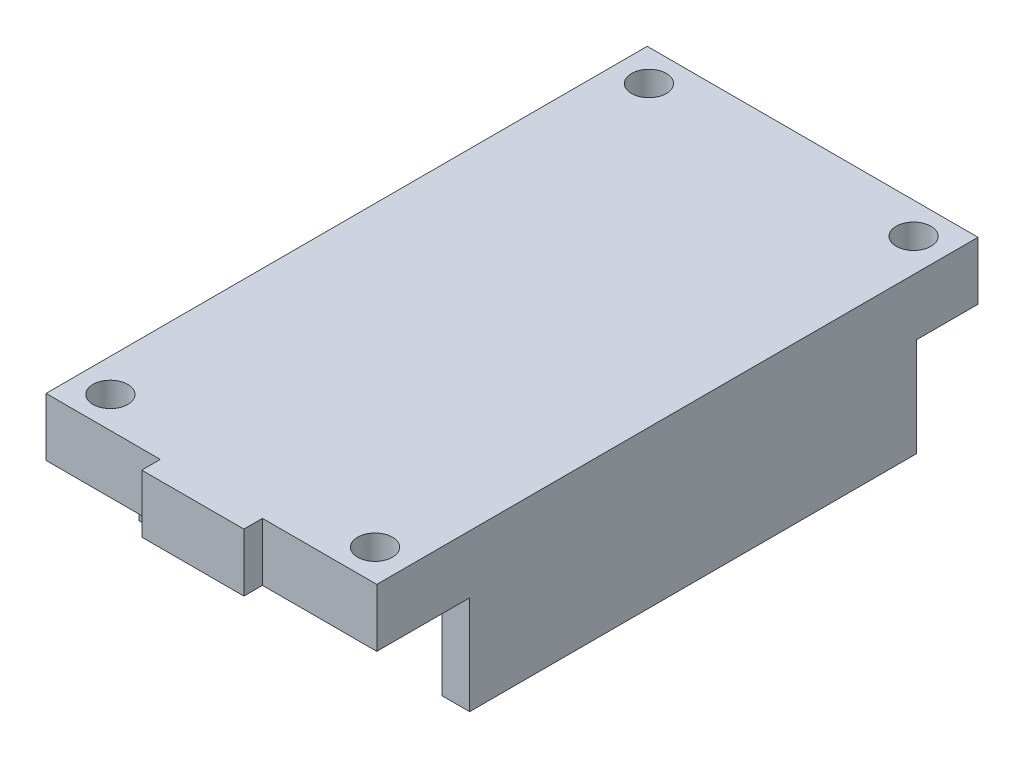
SolidWorks part; units mm, degrees
ref_plane "Front Plane" through (0, 0, 0) normal (0, 0, 1) x (1, 0, 0)
ref_plane "Top Plane" through (0, 0, 0) normal (0, 1, 0) x (1, 0, 0)
ref_plane "Right Plane" through (0, 0, 0) normal (1, 0, 0) x (0, 0, -1)
sketch "Sketch1" plane through (0, 0, 0) normal (0, 1, 0) x (1, 0, 0)
  line L0 (-4.4, -25.9) -> (4.4, -25.9) construction
  line L1 (-14.25, -25.9) -> (14.25, -25.9)
  line L2 (-14.25, -25.9) -> (-14.25, 25.9)
  line L3 (-14.25, 25.9) -> (14.25, 25.9)
  line L4 (14.25, -25.9) -> (14.25, 25.9)
  line L5 (-14.25, -25.9) -> (14.25, 25.9) construction
  line L6 (-14.25, 25.9) -> (14.25, -25.9) construction
  line L8 (-4.4, -25.9) -> (4.4, -25.9)
  line L9 (-4.4, -25.9) -> (-4.4, -27.5)
  line L10 (-4.4, -27.5) -> (4.4, -27.5)
  line L11 (4.4, -25.9) -> (4.4, -27.5)
  line L12 (-11.4, -23.2) -> (11.4, -23.2) construction
  line L13 (-11.4, -23.2) -> (-11.4, 23.2) construction
  line L14 (-11.4, 23.2) -> (11.4, 23.2) construction
  line L15 (11.4, -23.2) -> (11.4, 23.2) construction
  line L16 (-11.4, -23.2) -> (11.4, 23.2) construction
  line L17 (-11.4, 23.2) -> (11.4, -23.2) construction
  circle A0 centre (-11.4, 23.2) radius 1.5
  circle A1 centre (11.4, 23.2) radius 1.5
  circle A2 centre (11.4, -23.2) radius 1.5
  circle A3 centre (-11.4, -23.2) radius 1.5
  point P0 (0, 0)
  point P9 (0, -25.9)
  point P11 (0, 0)
  dimension "D7" = 3
  dimension "D1" = 28.5
  dimension "D2" = 51.8
  dimension "D3" = 8.8
  dimension "D4" = 1.6
  dimension "D5" = 22.8
  dimension "D6" = 46.4
extrude "Boss-Extrude1" add sketch "Sketch1" along normal blind 5 contours L1 L4 L3 L2 A3 A2 A1 A0 | L11 L1 L9 L10
sketch "Sketch2" plane through (0, 0, 0) normal (0, -1, 0) x (1, 0, 0)
  line L0 (14.25, -25.9) -> (14.25, -20.6) construction
  line L1 (14.25, 25.9) -> (14.25, -25.9) construction
  line L2 (14.25, 25.9) -> (14.25, 17.9) construction
  line L3 (-14.25, 25.9) -> (-14.25, -25.9) construction
  line L4 (14.25, 17.9) -> (11.85, 17.9)
  line L5 (14.25, 17.9) -> (14.25, -20.6)
  line L6 (14.25, -20.6) -> (11.85, -20.6)
  line L7 (11.85, 17.9) -> (11.85, -20.6)
  line L8 (-14.25, 17.9) -> (-11.85, 17.9)
  line L9 (-14.25, 17.9) -> (-14.25, -20.6)
  line L10 (-14.25, -20.6) -> (-11.85, -20.6)
  line L11 (-11.85, 17.9) -> (-11.85, -20.6)
  dimension "D1" = 5.3
  dimension "D2" = 8
  dimension "D3" = 2.4
extrude "Boss-Extrude2" add sketch "Sketch2" along normal blind 8.5
